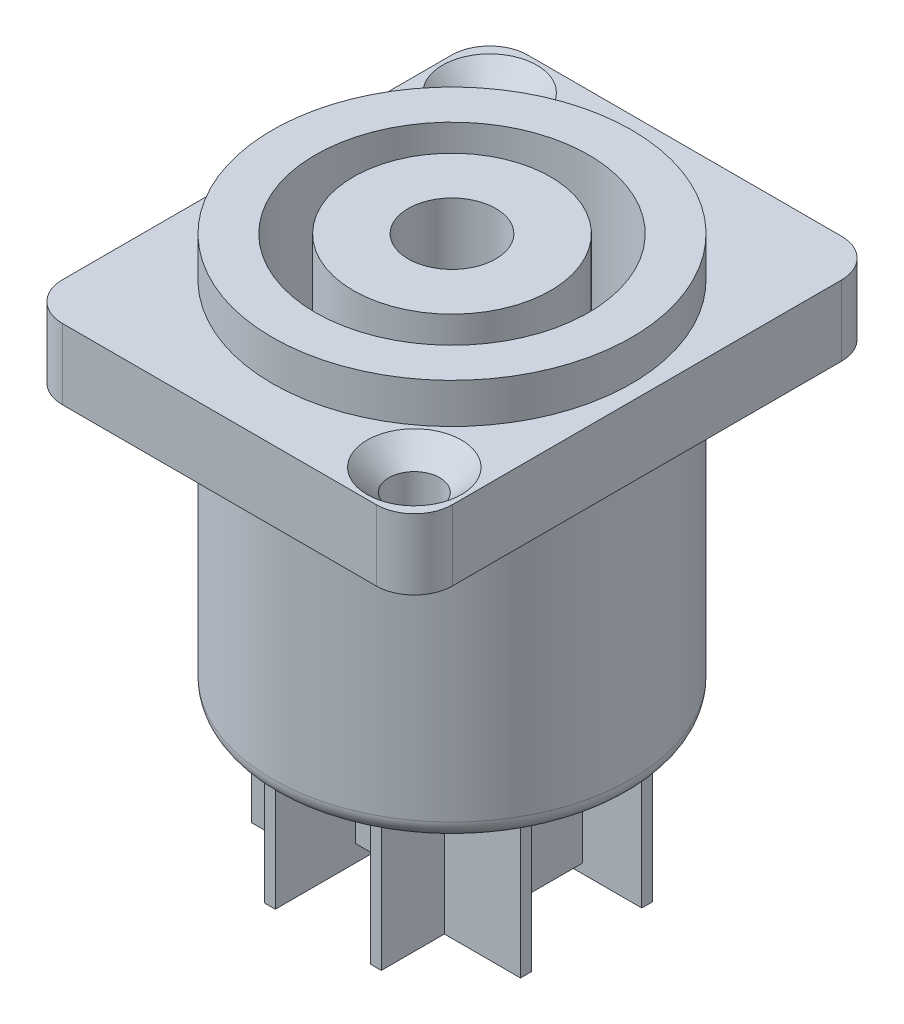
SolidWorks part; units mm, degrees
ref_plane "Front" through (0, 0, 0) normal (0, 0, 1) x (1, 0, 0)
ref_plane "Top" through (0, 0, 0) normal (0, 1, 0) x (1, 0, 0)
ref_plane "Right" through (0, 0, 0) normal (1, 0, 0) x (0, 0, -1)
sketch "Sketch1" plane through (0, 0, 0) normal (0, 1, 0) x (1, 0, 0)
  circle A0 centre (0, 0) radius 11.9888
  dimension "D1" = 23.9776
extrude "Boss-Extrude1" add sketch "Sketch1" against normal blind 19.431 and the other way blind 7.366
sketch "Sketch3" plane through (0, 0, 0) normal (0, 1, 0) x (1, 0, 0)
  line L1 (-13.0048, -15.5194) -> (13.0048, -15.5194)
  line L2 (-13.0048, -15.5194) -> (-13.0048, 15.5194)
  line L3 (-13.0048, 15.5194) -> (13.0048, 15.5194)
  line L4 (13.0048, -15.5194) -> (13.0048, 15.5194)
  line L5 (-13.0048, -15.5194) -> (13.0048, 15.5194) construction
  line L6 (-13.0048, 15.5194) -> (13.0048, -15.5194) construction
  point P0 (0, 0)
  dimension "D1" = 26.0096
  dimension "D2" = 31.0388
extrude "Boss-Extrude3" add sketch "Sketch3" along normal blind 4.699
sketch "Sketch6" plane through (0, 4.699, 0) normal (0, 1, 0) x (1, 0, 0)
  line L0 (13.0048, 15.5194) -> (-13.0048, 15.5194) construction
  line L1 (-13.0048, 15.5194) -> (-13.0048, -15.5194) construction
  line L2 (-13.0048, -15.5194) -> (13.0048, -15.5194) construction
  line L3 (13.0048, -15.5194) -> (13.0048, 15.5194) construction
  point P0 (-9.5758, 12.0904)
  point P1 (9.5758, -12.0904)
  point P10 (0, 0)
  dimension "D1" = 3.429
  dimension "D2" = 3.429
  dimension "D3" = 3.429
  dimension "D4" = 3.429
hole_wizard "CSK for M3 Flat Head Machine Screw2" positions "Sketch9" profile "Sketch10" countersink size "M3" standard "ANSI Metric" end condition through all
sketch "Sketch9" plane through (0, 4.699, 0) normal (0, 1, 0) x (1, 0, 0)
  point P0 (-9.5758, 12.0904)
  point P3 (9.5758, -12.0904)
sketch "Sketch10" plane through (-9.5758, 4.699, -12.0904) normal (1, 0, 0) x (0, 0, 1)
  line L0 (0, 0) -> (0, 24.13)
  line L1 (0, 24.13) -> (1.7, 24.13)
  line L2 (1.7, 24.13) -> (1.7, 1.45)
  line L3 (1.7, 1.45) -> (3.15, 0)
  line L5 (3.15, 0) -> (0, 0)
  line L6 (-1.7, 1.45) -> (-3.15, 0) construction
  line L11 (0, -6.35) -> (0, 107.95) construction
  dimension "Thru Hole Dia." = 3.4
  dimension "Thru Hole Depth" = 24.13
  dimension "Near C'Sink Dia." = 6.3
  dimension "Near C'Sink Angle" = 90
sketch "Sketch11" plane through (0, 7.366, 0) normal (0, 1, 0) x (1, 0, 0)
  circle A1 centre (0, 0) radius 6.5786
  circle A2 centre (0, 0) radius 9.1186
  circle A3 centre (0, 0) radius 9.1186
  dimension "D1" = 2.8702
  dimension "D2" = 2.54
extrude "Cut-Extrude1" cut sketch "Sketch11" against normal offset from surface (21.717 mm away) 5.08 up to face at (0, -19.431, 11.9888)
fillet "Fillet1" radius 2.54 4 edges at (13.0048, 2.3495, 15.5194) (-13.0048, 2.3495, 15.5194) (-13.0048, 2.3495, -15.5194) (13.0048, 2.3495, -15.5194)
sketch "Sketch12" plane through (0, 7.366, 0) normal (0, 1, 0) x (1, 0, 0)
  circle A0 centre (0, 0) radius 2.921
  dimension "D1" = 5.842
extrude "Cut-Extrude3" cut sketch "Sketch12" against normal up to surface (21.717 mm away) contours A0 up to face at (0, -14.351, 9.1186)
sketch "Sketch13" plane through (0, -19.431, 0) normal (0, -1, 0) x (1, 0, 0)
  line L1 (3.175, 0.3619) -> (-3.175, 0.3619)
  line L2 (-3.175, 0.3619) -> (-3.175, 8.6169)
  line L3 (-3.175, 8.6169) -> (-3.8989, 8.6169)
  line L4 (-3.8989, 8.6169) -> (-3.8989, 4.4069)
  line L5 (-3.8989, 4.4069) -> (-8.9789, 4.4069)
  line L7 (-8.9789, 3.683) -> (-3.8989, 3.683)
  line L8 (-3.8989, 3.683) -> (-3.8989, -3.683)
  line L41 (-8.9789, 4.4069) -> (-8.9789, 3.683)
  line L44 (0.9956, 0) -> (-0.9956, 0) construction
  line L45 (0, 0.273) -> (0, 1.1157) construction
  line L46 (-8.9789, -3.683) -> (-3.8989, -3.683)
  line L47 (-3.8989, -4.4069) -> (-8.9789, -4.4069)
  line L48 (-3.8989, -8.6169) -> (-3.8989, -4.4069)
  line L49 (-3.175, -8.6169) -> (-3.8989, -8.6169)
  line L50 (-3.175, -0.362) -> (-3.175, -8.6169)
  line L51 (3.175, -0.362) -> (-3.175, -0.362)
  line L52 (-8.9789, -4.4069) -> (-8.9789, -3.683)
  line L53 (0, 0.3619) -> (0, -0.3619) construction
  line L54 (3.175, -0.362) -> (3.175, -8.6169)
  line L55 (3.175, -8.6169) -> (3.8989, -8.6169)
  line L56 (3.8989, -8.6169) -> (3.8989, -4.4069)
  line L57 (3.8989, -4.4069) -> (8.9789, -4.4069)
  line L58 (8.9789, -4.4069) -> (8.9789, -3.683)
  line L59 (8.9789, -3.683) -> (3.8989, -3.683)
  line L60 (3.8989, 3.683) -> (3.8989, -3.683)
  line L61 (8.9789, 3.683) -> (3.8989, 3.683)
  line L62 (8.9789, 4.4069) -> (8.9789, 3.683)
  line L63 (3.8989, 4.4069) -> (8.9789, 4.4069)
  line L64 (3.8989, 8.6169) -> (3.8989, 4.4069)
  line L65 (3.175, 8.6169) -> (3.8989, 8.6169)
  line L66 (3.175, 0.3619) -> (3.175, 8.6169)
  point P12 (-3.8989, 0)
  point P21 (0, 0)
  dimension "D1" = 0.7239
  dimension "D2" = 8.255
  dimension "D3" = 5.08
  dimension "D4" = 7.366
  dimension "D5" = 6.35
extrude "Boss-Extrude4" add sketch "Sketch13" along normal blind 9.525 contours L1 L2 L3 L4 L5 L41 L7 L8 L46 L52 L47 L48 L49 L50 L51 L54 L55 L56 L57 L58 L59 L60 L61 L62 L63 L64 L65 L66
sketch "Sketch14" plane through (0, -19.431, 0) normal (0, -1, 0) x (1, 0, 0)
  line L0 (-3.8989, 3.683) -> (-3.8989, -3.683) construction
  line L1 (2.3813, 3.5369) -> (-2.3813, 3.5369)
  line L2 (2.3813, 3.5369) -> (2.3813, 4.0449)
  line L3 (2.3813, 4.0449) -> (-2.3813, 4.0449)
  line L4 (-2.3813, 3.5369) -> (-2.3813, 4.0449)
  line L5 (2.3813, 3.5369) -> (-2.3813, 4.0449) construction
  line L6 (2.3813, 4.0449) -> (-2.3813, 3.5369) construction
  line L7 (-6.3119, -2.3812) -> (-5.8039, -2.3812)
  line L8 (-6.3119, -2.3812) -> (-6.3119, 2.3813)
  line L9 (-6.3119, 2.3813) -> (-5.8039, 2.3813)
  line L10 (-5.8039, -2.3812) -> (-5.8039, 2.3813)
  line L11 (-6.3119, -2.3812) -> (-5.8039, 2.3813) construction
  line L12 (-6.3119, 2.3813) -> (-5.8039, -2.3812) construction
  line L13 (3.175, 0.3619) -> (-3.175, 0.3619) construction
  line L14 (0, 0) -> (0, 7.5631) construction
  line L15 (6.3119, -2.3812) -> (5.8039, -2.3812)
  line L16 (5.8039, -2.3812) -> (5.8039, 2.3813)
  line L17 (6.3119, 2.3813) -> (5.8039, 2.3813)
  line L18 (6.3119, -2.3812) -> (6.3119, 2.3813)
  point P0 (0, 3.7909)
  point P5 (-6.0579, 0)
  dimension "D1" = 0.508
  dimension "D2" = 4.7625
  dimension "D3" = 1.905
  dimension "D4" = 3.175
extrude "Boss-Extrude5" add sketch "Sketch14" along normal blind 7.62
fillet "Fillet2" radius 1.27 1 edges at (0, -19.431, 11.9888)
